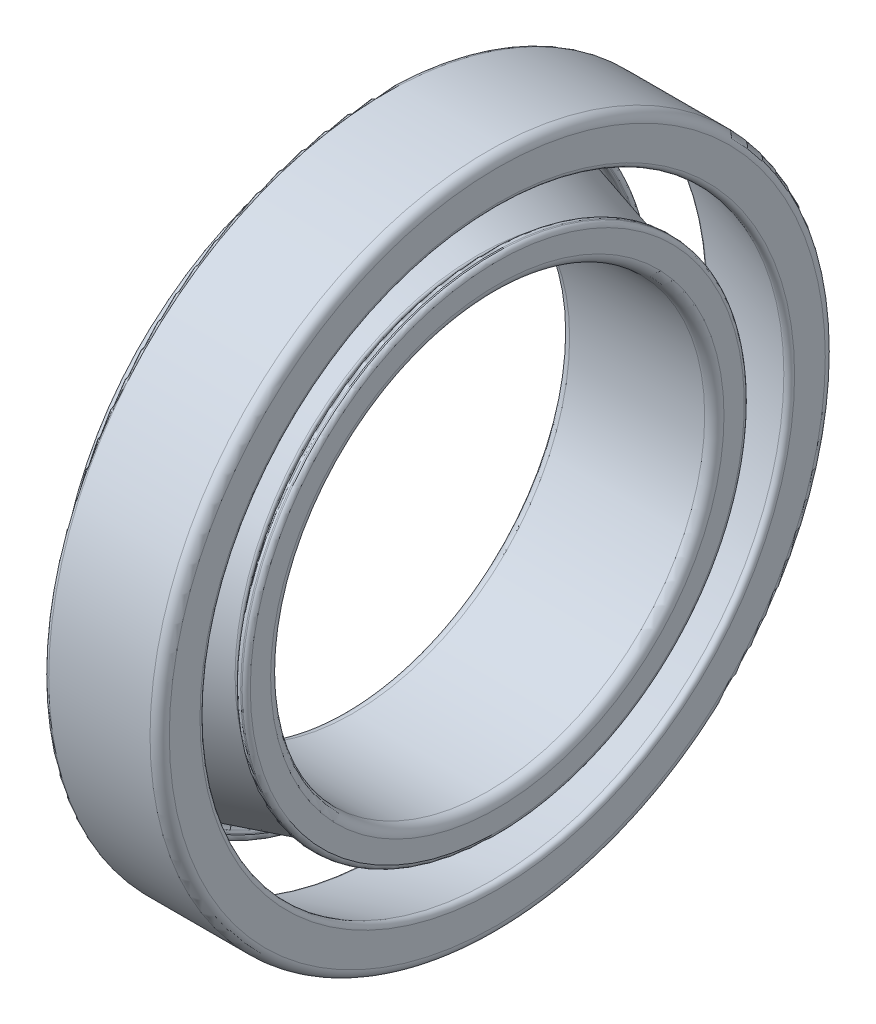
SolidWorks part; units mm, degrees
ref_plane "Front Plane" through (0, 0, 0) normal (0, 0, 1) x (1, 0, 0)
ref_plane "Top Plane" through (0, 0, 0) normal (0, 1, 0) x (1, 0, 0)
ref_plane "Right Plane" through (0, 0, 0) normal (1, 0, 0) x (0, 0, -1)
sketch "Sketch1" plane through (0, 0, 0) normal (0, 0, 1) x (1, 0, 0)
  line L0 (0, 0) -> (105.028, 0) construction
  line L1 (0, 68) -> (0, 61.6392)
  line L2 (-1.268, 60.6758) -> (-23.268, 66.7964)
  line L3 (-24, 69) -> (-24, 67.7598)
  line L4 (-23, 70) -> (-2, 70)
  line L5 (-12.268, 63.7361) -> (-38.6522, -31.0996) construction
  line L6 (-26.2581, 56.5753) -> (-3.9862, 50.3791)
  line L7 (-2.2446, 51.3625) -> (-2.1949, 51.5415)
  line L8 (-0.9634, 52.2368) -> (-0.732, 52.1724)
  line L9 (0, 51.209) -> (0, 47)
  line L10 (-2, 45) -> (-30, 45)
  line L11 (-32, 47) -> (-32, 58.2391)
  line L12 (-29.4639, 60.166) -> (-27.8871, 59.7273)
  line L13 (-27.1917, 58.4958) -> (-27.2415, 58.3168)
  arc A0 (0, 68) -> (-2, 70) centre (-2, 68) ccw
  arc A1 (-24, 67.7598) -> (-23.268, 66.7964) centre (-23, 67.7598) ccw
  arc A2 (0, 61.6392) -> (-1.268, 60.6758) centre (-1, 61.6392) cw
  arc A3 (-24, 69) -> (-23, 70) centre (-23, 69) cw
  arc A4 (-27.689, 57.952) -> (-26.8016, 56.3805) centre (-27.6206, 56.9544) ccw
  arc A5 (-3.6214, 49.9316) -> (-2.0499, 50.819) centre (-2.6237, 50) ccw
  arc A6 (0, 47) -> (-2, 45) centre (-2, 47) cw
  arc A7 (-30, 45) -> (-32, 47) centre (-30, 47) cw
  arc A8 (-32, 58.2391) -> (-29.4639, 60.166) centre (-30, 58.2391) cw
  arc A9 (-0.732, 52.1724) -> (0, 51.209) centre (-1, 51.209) cw
  arc A10 (-2.1949, 51.5415) -> (-0.9634, 52.2368) centre (-1.2314, 51.2734) cw
  arc A11 (-27.8871, 59.7273) -> (-27.1917, 58.4958) centre (-28.1552, 58.7639) cw
  arc A12 (-2.0499, 50.819) -> (-2.2446, 51.3625) centre (-1.7629, 51.2285) cw
  arc A13 (-3.6214, 49.9316) -> (-3.9862, 50.3791) centre (-4.1202, 49.8973) ccw
  arc A14 (-26.8016, 56.3805) -> (-26.2581, 56.5753) centre (-26.3921, 56.0936) cw
  arc A15 (-27.689, 57.952) -> (-27.2415, 58.3168) centre (-27.7232, 58.4509) ccw
  point P9 (-30, 0)
  point P10 (0, 0)
  point P13 (0, 70)
  point P16 (-24, 70)
  point P21 (-24, 67)
  point P31 (-15.1221, 53.4772)
  point P35 (-24, 70)
  point P38 (0, 45)
  point P41 (-32, 45)
  point P46 (0, 51.9688)
  point P49 (-1.9268, 52.5049)
  point P54 (-2.3557, 50.9634)
  dimension "D5" = 2
  dimension "D6" = 1
  dimension "D9" = 2
  dimension "D10" = 2
  dimension "D15" = 1
  dimension "D16" = 1
  dimension "D17" = 2
  dimension "D18" = 1
  dimension "D19" = 0.5
  dimension "D1" = 24
  dimension "D2" = 70
  dimension "D3" = 30
  dimension "D4" = 67
  dimension "D7" = 1.6
  dimension "D8" = 2
  dimension "D11" = 45
  dimension "D12" = 32
  dimension "D13" = 32
  dimension "D14" = 50
revolve "Revolve1" add sketch "Sketch1" angle 360 about L0
